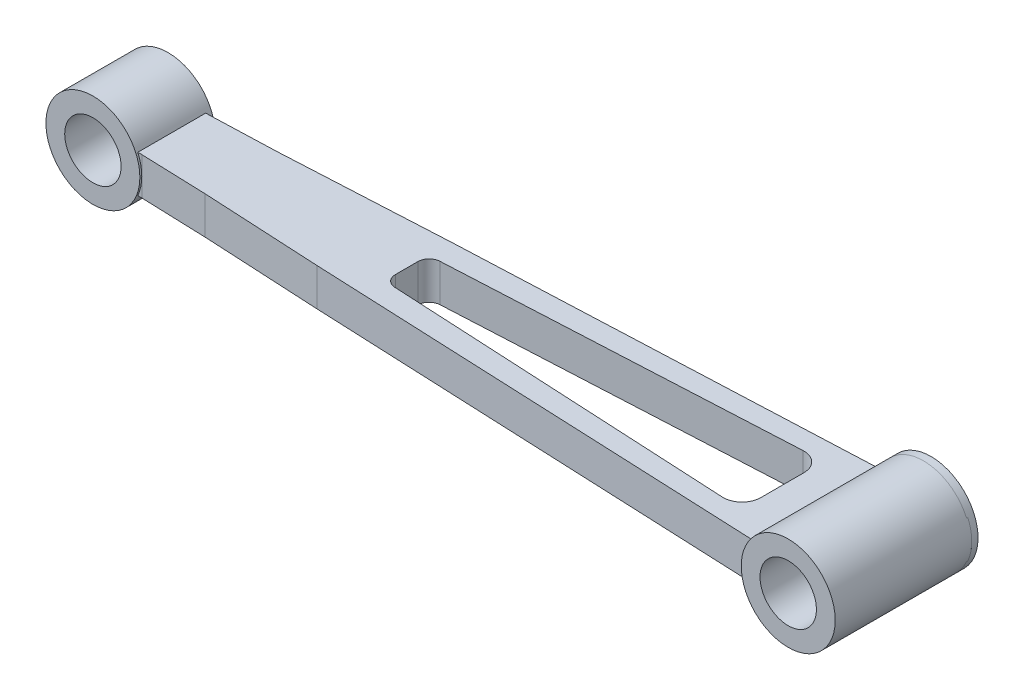
SolidWorks part; units mm, degrees
ref_plane "Front Plane" through (0, 0, 0) normal (0, 0, 1) x (1, 0, 0)
ref_plane "Top Plane" through (0, 0, 0) normal (0, 1, 0) x (1, 0, 0)
ref_plane "Right Plane" through (0, 0, 0) normal (1, 0, 0) x (0, 0, -1)
sketch "Sketch1" plane through (0, 0, 0) normal (0, 1, 0) x (1, 0, 0)
  line L0 (0, 0) -> (0, 9)
  line L2 (0, 0) -> (0, -9)
  line L3 (0, -9) -> (0, -9.0714)
  line L4 (0, 9) -> (25, 9)
  line L5 (25, 9) -> (25, -9.0714)
  line L8 (25, -9.0714) -> (42.5, -9.6825)
  line L9 (42.5, 9.6111) -> (42.5, -9.6825)
  line L10 (42.5, 9.6111) -> (86.39, 11.9113)
  line L11 (42.5, -9.6825) -> (73.89, -11.3276)
  line L12 (86.39, 3) -> (86.39, 0)
  line L13 (86.39, 0) -> (86.39, -3)
  line L14 (89.2348, -5.996) -> (181.1313, -10.7567)
  line L15 (186.39, -5.7634) -> (186.39, 5.6995)
  line L16 (181.1348, 10.693) -> (89.2369, 5.9961)
  line L17 (86.39, 11.9113) -> (207.06, 17.1799)
  line L18 (73.89, -11.3276) -> (207.06, -17.1419)
  line L19 (207.06, 17.1799) -> (207.06, -17.1419)
  line L20 (207.06, 17.1799) -> (219.56, 17.1799)
  line L21 (219.56, 17.1799) -> (219.56, -17.1419)
  line L22 (219.56, -17.1419) -> (207.06, -17.1419)
  line L23 (25, 9) -> (42.5, 9.6111)
  line L24 (0, -9.0714) -> (25, -9.0714)
  arc A0 (86.39, 3) -> (89.2369, 5.9961) centre (89.39, 3) cw
  arc A1 (89.2348, -5.996) -> (86.39, -3) centre (89.39, -3) cw
  arc A2 (186.39, -5.7634) -> (181.1313, -10.7567) centre (181.39, -5.7634) cw
  arc A3 (186.39, 5.6995) -> (181.1348, 10.693) centre (181.39, 5.6995) ccw
  point P5 (12.5, 9)
  dimension "D12" = 3
  dimension "D13" = 3
  dimension "D14" = 5
  dimension "D1" = 9
  dimension "D2" = 9
  dimension "D3" = 25
  dimension "D6" = 30
  dimension "D8" = 43.89
  dimension "D9" = 31.39
  dimension "D15" = 100
  dimension "D16" = 3
  dimension "D17" = 3
  dimension "D20" = 20.67
  dimension "D21" = 20.67
  dimension "D22" = 12.5
extrude "Boss-Extrude6" add sketch "Sketch1" along normal blind 10 contours L19 L17 L10 L9 L11 L18 A3 L15 A2 L14 A1 L13 L12 A0 L16 | L23 L5 L8 L9 | L3 L24 L5 L4 L0 L2 | L22 L21 L20 L19
sketch "Sketch12" plane through (0, 0, 9.0714) normal (0, 0, 1) x (1, 0, 0)
  circle A0 centre (12.5, 5) radius 12.5
  dimension "D1" = 25
extrude "Boss-Extrude7" add sketch "Sketch12" against normal blind 19
sketch "Sketch13" plane through (0, 0, 9.0714) normal (0, 0, 1) x (1, 0, 0)
  line L0 (0, 10) -> (1.0436, 10)
  line L1 (1.0436, 10) -> (1.0436, 0)
  line L2 (1.0436, 0) -> (0, 0)
  line L3 (0, 0) -> (0, 10)
extrude "Cut-Extrude7" cut sketch "Sketch13" against normal blind 28 contours L1 L2 L3 L0
sketch "Sketch14" plane through (0, 0, 9.0714) normal (0, 0, 1) x (1, 0, 0)
  circle A0 centre (12.5, 5) radius 12.5
  dimension "D1" = 25
extrude "Boss-Extrude8" add sketch "Sketch14" against normal blind 19
sketch "Sketch15" plane through (0, 0, 9.0714) normal (0, 0, 1) x (1, 0, 0)
  circle A0 centre (12.5, 5) radius 12.5
  dimension "D1" = 25
extrude "Boss-Extrude9" add sketch "Sketch15" along normal blind 0.5
sketch "Sketch16" plane through (0, 0, -9.9286) normal (0, 0, -1) x (-1, 0, 0)
  circle A0 centre (-12.5, 5) radius 12.5
  dimension "D1" = 25
extrude "Boss-Extrude10" add sketch "Sketch16" along normal blind 0.5
sketch "Sketch17" plane through (0, 0, -10.4286) normal (0, 0, -1) x (-1, 0, 0)
  circle A0 centre (-12.5, 5) radius 7.5
  dimension "D1" = 15
extrude "Cut-Extrude8" cut sketch "Sketch17" against normal through all
sketch "Sketch18" plane through (0, 0, 17.1419) normal (0, 0, 1) x (1, 0, 0)
  line L2 (207.06, 10) -> (207.06, 0) construction
  circle A0 centre (207.06, 5) radius 12.5
  dimension "D2" = 25
extrude "Boss-Extrude12" add sketch "Sketch18" against normal blind 34 contours A0
sketch "Sketch19" plane through (0, 0, 17.1419) normal (0, 0, 1) x (1, 0, 0)
  circle A0 centre (207.06, 5) radius 12.5
  dimension "D1" = 25
extrude "Boss-Extrude13" add sketch "Sketch19" along normal blind 2
sketch "Sketch20" plane through (0, 0, 19.1419) normal (0, 0, 1) x (1, 0, 0)
  line L0 (218.5164, 10) -> (219.56, 10)
  line L1 (219.56, 10) -> (219.56, 5)
  circle A0 centre (207.06, 5) radius 12.5 construction
  arc A1 (218.5164, 0) -> (219.56, 5) centre (207.06, 5) ccw construction
  arc A2 (219.56, 5) -> (218.5164, 10) centre (207.06, 5) ccw
extrude "Cut-Extrude9" cut sketch "Sketch20" against normal through all
sketch "Sketch21" plane through (0, 0, 19.1419) normal (0, 0, 1) x (1, 0, 0)
  line L0 (218.5164, 0) -> (219.56, 0)
  line L1 (219.56, 0) -> (219.56, 5)
  arc A0 (219.56, 5) -> (218.5164, 0) centre (207.06, 5) cw
extrude "Cut-Extrude10" cut sketch "Sketch21" against normal through all
sketch "Sketch22" plane through (0, 0, -16.8581) normal (0, 0, -1) x (-1, 0, 0)
  line L0 (-207.06, 10) -> (-207.06, 0) construction
  circle A0 centre (-207.06, 5) radius 12.4999
  dimension "D1" = 24.9997
extrude "Boss-Extrude14" add sketch "Sketch22" along normal blind 2
sketch "Sketch23" plane through (0, 0, -18.8581) normal (0, 0, -1) x (-1, 0, 0)
  circle A0 centre (-207.06, 5) radius 7.5
  dimension "D1" = 15
extrude "Cut-Extrude11" cut sketch "Sketch23" against normal through all
